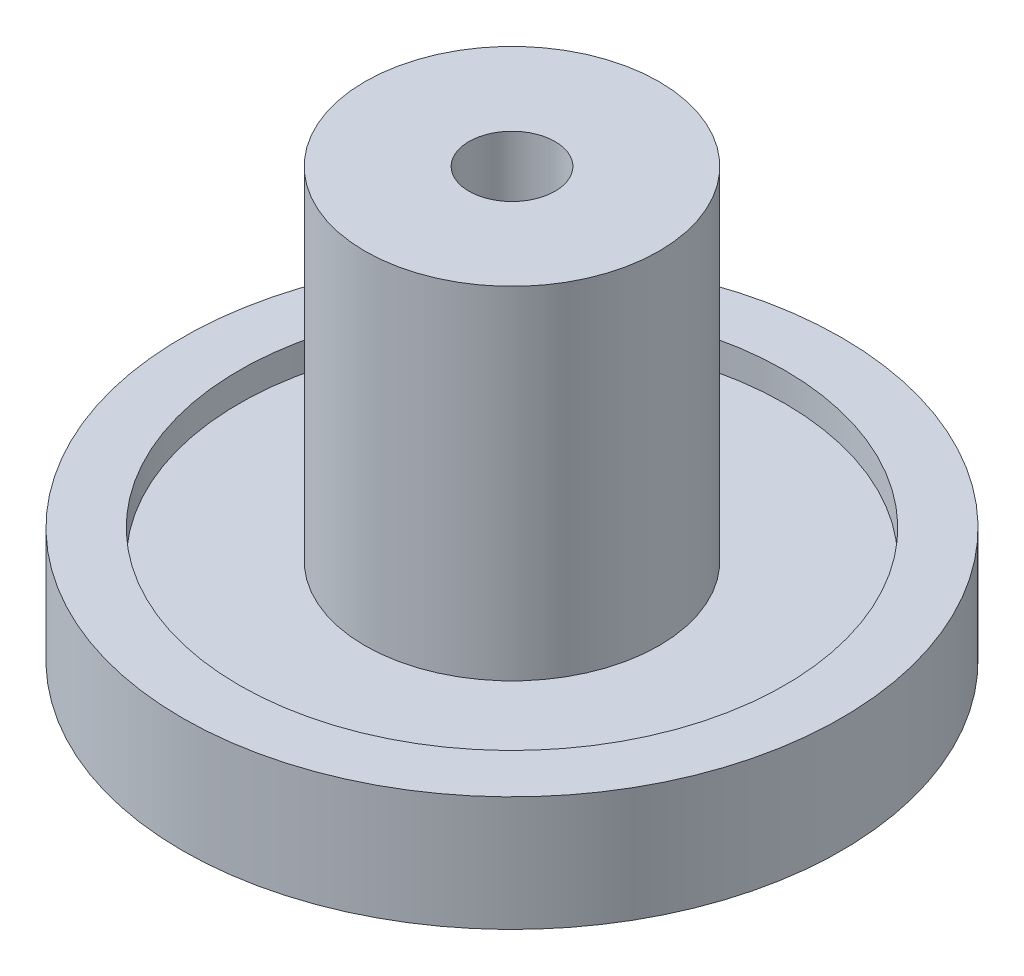
SolidWorks part; units mm, degrees
material "Nylon 101"
ref_plane "Front Plane" through (0, 0, 0) normal (0, 0, 1) x (1, 0, 0)
ref_plane "Top Plane" through (0, 0, 0) normal (0, 1, 0) x (1, 0, 0)
ref_plane "Right Plane" through (0, 0, 0) normal (1, 0, 0) x (0, 0, -1)
sketch "Sketch1" plane through (0, 0, 0) normal (0, 0, 1) x (1, 0, 0)
  line L0 (0, 0) -> (0, 14.9) construction
  line L1 (1.5, 14.9) -> (1.5, 0)
  line L2 (1.5, 0) -> (3.5, 0)
  line L3 (3.5, 0) -> (3.5, 1.2)
  line L4 (3.5, 1.2) -> (9.5, 1.2)
  line L5 (9.5, 1.2) -> (9.5, 0)
  line L6 (9.5, 0) -> (11.4776, 0)
  line L7 (11.4776, 0) -> (11.4776, 4)
  line L8 (11.4776, 4) -> (9.5, 4)
  line L9 (9.5, 4) -> (9.5, 3)
  line L10 (9.5, 3) -> (5.1181, 3)
  line L11 (5.1181, 3) -> (5.1181, 14.9)
  line L12 (5.1181, 14.9) -> (1.5, 14.9)
  line L13 (0, 14.9) -> (1.5, 14.9) construction
  line L14 (0, 0) -> (1.5, 0) construction
  dimension "D1" = 3
  dimension "D2" = 7
  dimension "D3" = 19
  dimension "D4" = 22.9552
  dimension "D5" = 10.2362
  dimension "D6" = 1.2
  dimension "D7" = 1
  dimension "D8" = 4
  dimension "D9" = 14.9
revolve "20 and 58" add sketch "Sketch1" angle 360 about L0
